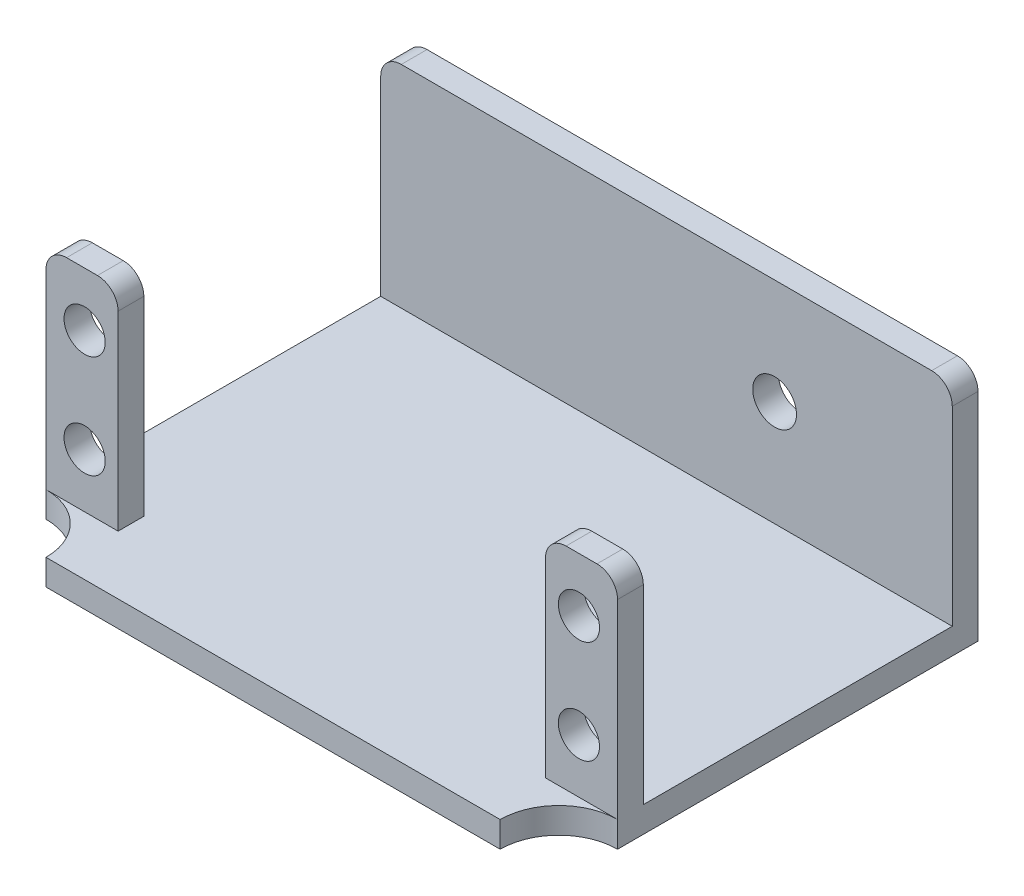
SolidWorks part; units mm, degrees
ref_plane "Front" through (0, 0, 0) normal (0, 0, 1) x (1, 0, 0)
ref_plane "Top" through (0, 0, 0) normal (0, 1, 0) x (1, 0, 0)
ref_plane "Right" through (0, 0, 0) normal (1, 0, 0) x (0, 0, -1)
sketch "Sketch1" plane through (0, 0, 0) normal (0, 1, 0) x (1, 0, 0)
  line L1 (0, 0) -> (55.5, 0)
  line L2 (0, 0) -> (0, 38.2)
  line L3 (0, 38.2) -> (55.5, 38.2)
  line L4 (55.5, 0) -> (55.5, 38.2)
  dimension "D1" = 38.2
  dimension "D2" = 55.5
extrude "bracketBase" add sketch "Sketch1" along normal blind 2.5
ref_plane "referencePlane1" through (0, 0, -8.2) normal (0, 0, 1) x (1, 0, 0)
sketch "Sketch2" plane through (0, 0, -8.2) normal (0, 0, 1) x (1, 0, 0)
  line L0 (27.75, 2.5) -> (27.75, 23) construction
  line L1 (0, 2.5) -> (7, 2.5)
  line L2 (0, 2.5) -> (0, 23)
  line L3 (0, 23) -> (7, 23)
  line L4 (7, 2.5) -> (7, 23)
  line L5 (0, 2.5) -> (55.5, 2.5) construction
  line L6 (55.5, 23) -> (48.5, 23)
  line L7 (48.5, 2.5) -> (48.5, 23)
  line L8 (55.5, 2.5) -> (48.5, 2.5)
  line L9 (55.5, 2.5) -> (55.5, 23)
  dimension "D1" = 20.5
  dimension "D2" = 7
extrude "servoMountingHoleTabs" add sketch "Sketch2" along normal blind 2.5
sketch "Sketch3" plane through (0, 0, -5.7) normal (0, 0, 1) x (1, 0, 0)
  line L0 (0, 12.75) -> (7, 12.75) construction
  line L3 (0, 23) -> (0, 2.5) construction
  line L4 (7, 2.5) -> (7, 23) construction
  line L5 (7, 23) -> (0, 23) construction
  line L6 (27.75, 2.5) -> (27.75, 23) construction
  line L7 (0, 2.5) -> (55.5, 2.5) construction
  circle A0 centre (3.75, 17.75) radius 2
  circle A1 centre (3.75, 7.75) radius 2
  circle A2 centre (51.75, 7.75) radius 2
  circle A3 centre (51.75, 17.75) radius 2
  dimension "D1" = 4
  dimension "D2" = 3.75
  dimension "D3" = 5.25
extrude "servoMountingHoles" cut sketch "Sketch3" against normal blind 2.5
sketch "Sketch4" plane through (0, 0, 0) normal (0, 1, 0) x (1, 0, 0)
  line L0 (55.5, 8.2) -> (55.5, 38.2) construction
  line L1 (0, 38.2) -> (55.5, 38.2)
  line L2 (0, 38.2) -> (0, 40.7)
  line L3 (0, 40.7) -> (55.5, 40.7)
  line L4 (55.5, 38.2) -> (55.5, 40.7)
  dimension "D1" = 2.5
extrude "baseWall" add sketch "Sketch4" along normal up to surface (23 mm away) up to face at (3.5, 23, -6.95)
sketch "Sketch5" plane through (0, 0, -38.2) normal (0, 0, 1) x (1, 0, 0)
  line L0 (0, 12.75) -> (55.5, 12.75) construction
  line L1 (0, 23) -> (0, 2.5) construction
  line L2 (55.5, 2.5) -> (55.5, 23) construction
  circle A0 centre (38.25, 12.75) radius 2.125
  dimension "D1" = 4.25
  dimension "D2" = 17.25
extrude "M4mountingHole" cut sketch "Sketch5" against normal blind 2.5
sketch "Sketch6" plane through (0, 2.5, 0) normal (0, 1, 0) x (1, 0, 0)
  circle A0 centre (0, 0) radius 5.7
  circle A1 centre (55.5, 0) radius 5.7
extrude "baseTrim" cut sketch "Sketch6" against normal blind 2.5
fillet "Fillet1" radius 2 6 edges at (7, 23, -6.95) (48.5, 23, -6.95) (0, 23, -6.95) (55.5, 23, -6.95) (55.5, 23, -39.45) (0, 23, -39.45)
sketch "Sketch7" plane through (0, 0, -40.7) normal (0, 0, -1) x (-1, 0, 0)
  line L0 (-27.75, 0) -> (-27.75, 23) construction
  line L1 (-55.5, 0) -> (0, 0) construction
  line L2 (-2, 23) -> (-53.5, 23) construction
  circle A0 centre (-38.25, 12.75) radius 2.125 construction
  circle A1 centre (-38.25, 12.75) radius 2.125 construction
  circle A2 centre (-17.25, 12.75) radius 2.125
extrude "Cut-Extrude1" cut sketch "Sketch7" against normal blind 10
sketch "Sketch8" plane through (0, 0, -38.2) normal (0, 0, 1) x (1, 0, 0)
  circle A2 centre (17.25, 12.75) radius 2.125 construction
  circle A3 centre (17.25, 12.75) radius 2.125
extrude "Boss-Extrude1" add sketch "Sketch8" against normal up to surface (2.5 mm away) up to face at (19.375, 12.75, -40.7)
